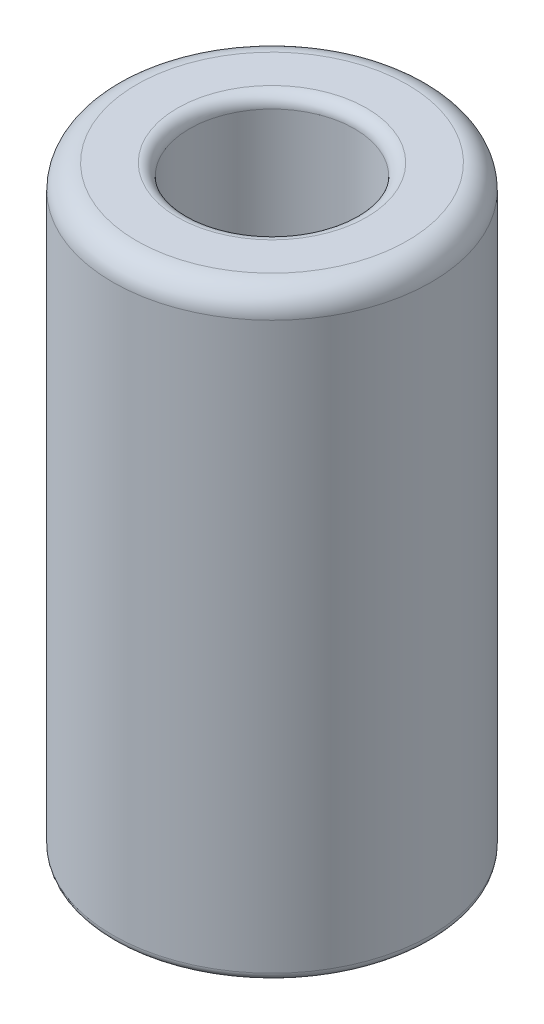
SolidWorks part; units mm, degrees
ref_plane "Ebene vorne" through (0, 0, 0) normal (0, 0, 1) x (1, 0, 0)
ref_plane "Ebene oben" through (0, 0, 0) normal (0, 1, 0) x (1, 0, 0)
ref_plane "Ebene rechts" through (0, 0, 0) normal (1, 0, 0) x (0, 0, -1)
sketch "Sketch1" plane through (0, 0, 0) normal (0, 1, 0) x (1, 0, 0)
  circle A0 centre (0, 0) radius 20
  dimension "D1" = 40
extrude "Boss-Extrude1" add sketch "Sketch1" along normal blind 35
sketch "Sketch2" plane through (0, 0, 0) normal (0, -1, 0) x (1, 0, 0)
  circle A0 centre (0, 0) radius 12.75
  dimension "D1" = 25.5
extrude "Cut-Extrude1" cut sketch "Sketch2" against normal up to surface (35 mm away) up to face at (0, 35, 20)
sketch "Sketch3" plane through (0, 35, 0) normal (0, 1, 0) x (1, 0, 0)
  circle A0 centre (0, 0) radius 20
extrude "Boss-Extrude2" add sketch "Sketch3" along normal blind 5
sketch "Sketch4" plane through (0, 35, 0) normal (0, -1, 0) x (1, 0, 0)
  circle A0 centre (0, 0) radius 12.75
  circle A3 centre (0, 0) radius 12.75 construction
extrude "Cut-Extrude2" cut sketch "Sketch4" against normal blind 10 draft 45
sketch "Sketch5" plane through (0, 40, 0) normal (0, 1, 0) x (1, 0, 0)
  circle A0 centre (0, 0) radius 20
  circle A1 centre (0, 0) radius 20 construction
extrude "Boss-Extrude3" add sketch "Sketch5" along normal blind 35
sketch "Sketch6" plane through (0, 75, 0) normal (0, 1, 0) x (1, 0, 0)
  circle A0 centre (0, 0) radius 10.375
  dimension "D1" = 20.75
extrude "Cut-Extrude3" cut sketch "Sketch6" against normal blind 33
fillet "Fillet1" radius 1.5 1 edges at (0, 0, -12.75)
fillet "Fillet2" radius 1.5 1 edges at (0, 75, 10.375)
fillet "Fillet3" radius 3 1 edges at (0, 75, 20)
fillet "Fillet4" radius 1 1 edges at (0, 0, 20)
